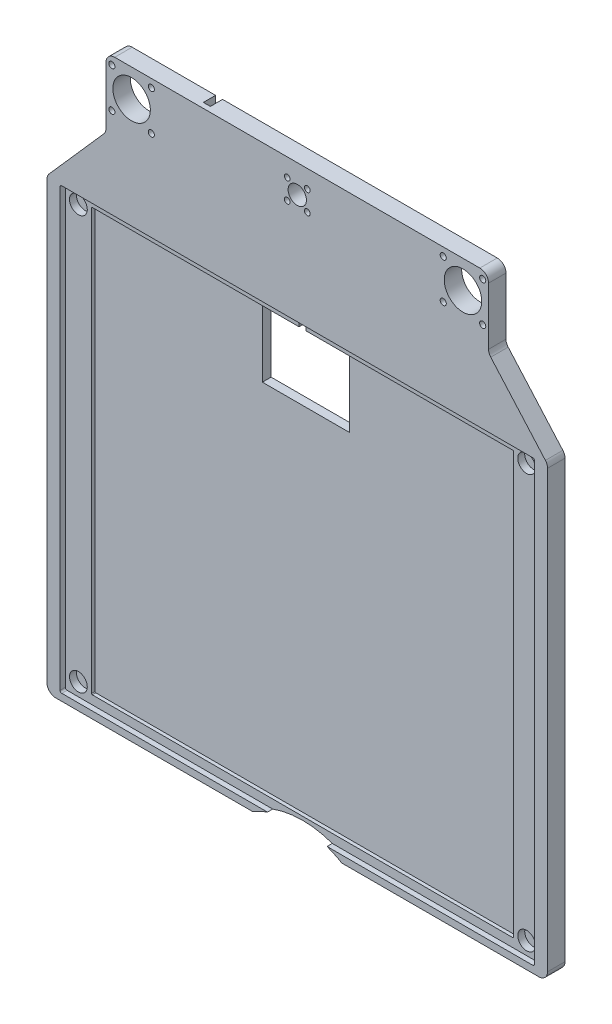
SolidWorks part; units mm, degrees
ref_plane "Alzado" through (0, 0, 0) normal (0, 0, 1) x (1, 0, 0)
ref_plane "Planta" through (0, 0, 0) normal (0, 1, 0) x (1, 0, 0)
ref_plane "Vista lateral" through (0, 0, 0) normal (1, 0, 0) x (0, 0, -1)
sketch "Model" plane through (0, 0, 0) normal (0, 0, 1) x (1, 0, 0)
  line L0 (-155.7898, 91.0382) -> (-155.7898, 58.2051)
  line L1 (-46.1298, -238.9618) -> (-46.1298, 159.2002) construction
  line L2 (-189.6298, 16.0382) -> (97.3702, 16.0382) construction
  line L3 (37.5552, 91.3532) -> (60.1852, 68.7232) construction
  line L4 (-129.8148, 91.3532) -> (-152.4448, 68.7232) construction
  line L5 (-141.1298, 80.0382) -> (48.8702, 80.0382) construction
  line L6 (-157.039, 54.8988) -> (64.7794, 54.8988) construction
  line L8 (63.5302, 58.2051) -> (63.5302, 91.0382)
  line L10 (96.121, 19.3445) -> (64.7794, 54.8988)
  line L14 (58.5302, 96.0382) -> (-150.7898, 96.0382)
  line L15 (-184.6298, -238.9618) -> (92.3702, -238.9618)
  line L16 (-189.6298, 16.0382) -> (-189.6298, -233.9618)
  line L17 (97.3702, 16.0382) -> (97.3702, -233.9618)
  line L91 (-188.3806, 19.3445) -> (-157.039, 54.8988)
  arc A0 (92.3702, -238.9618) -> (97.3702, -233.9618) centre (92.3702, -233.9618) ccw
  arc A1 (-189.6298, -233.9618) -> (-184.6298, -238.9618) centre (-184.6298, -233.9618) ccw
  arc A2 (-150.7898, 96.0382) -> (-155.7898, 91.0382) centre (-150.7898, 91.0382) ccw
  arc A3 (63.5302, 91.0382) -> (58.5302, 96.0382) centre (58.5302, 91.0382) ccw
  arc A4 (97.3702, 16.0382) -> (96.121, 19.3445) centre (92.3702, 16.0382) ccw
  arc A5 (-188.3806, 19.3445) -> (-189.6298, 16.0382) centre (-184.6298, 16.0382) ccw
  arc A6 (64.7794, 54.8988) -> (63.5302, 58.2051) centre (68.5302, 58.2051) cw
  arc A7 (-157.039, 54.8988) -> (-155.7898, 58.2051) centre (-160.7898, 58.2051) ccw
  circle A8 centre (48.8702, 80.0382) radius 10.75
  circle A9 centre (37.5552, 68.7232) radius 1.75
  circle A10 centre (60.1852, 68.7232) radius 1.75
  circle A11 centre (60.1852, 91.3532) radius 1.75
  circle A12 centre (37.5552, 91.3532) radius 1.75
  circle A13 centre (-129.8148, 91.3532) radius 1.75
  circle A14 centre (-152.4448, 91.3532) radius 1.75
  circle A15 centre (-152.4448, 68.7232) radius 1.75
  circle A16 centre (-129.8148, 68.7232) radius 1.75
  circle A17 centre (-141.1298, 80.0382) radius 10.75
  circle A18 centre (-46.1298, 80.0382) radius 5.25
  circle A19 centre (-51.8798, 85.7882) radius 1.65
  circle A20 centre (-40.3798, 85.7882) radius 1.65
  circle A21 centre (-40.3798, 74.2882) radius 1.65
  circle A22 centre (-51.8798, 74.2882) radius 1.65
  dimension "D1" = 5
  dimension "D2" = 5
  dimension "D3" = 5
  dimension "D13" = 5
  dimension "D14" = 5
  dimension "D15" = 5
  dimension "D18" = 5
  dimension "D19" = 5
  dimension "D20" = 21.5
  dimension "D8" = 3.5
  dimension "D5" = 10.5
  dimension "D7" = 3.3
  dimension "D4" = 287
  dimension "D16" = 48.603
  dimension "D6" = 95
  dimension "D12" = 5.75
  dimension "D22" = 5.75
  dimension "D23" = 11.315
  dimension "D24" = 11.315
  dimension "D25" = 16
  dimension "D26" = 335
  dimension "D27" = 109.66
  dimension "D28" = 109.66
  dimension "D29" = 255
  dimension "D17" = 48.603
  dimension "D9" = 2
  dimension "D21" = 2
  dimension "D10" = 2
  dimension "D11" = 2
extrude "Saliente-Extruir1" add sketch "Model" along normal blind 10
sketch "Croquis1" plane through (0, 0, 10) normal (0, 0, 1) x (1, 0, 0)
  line L0 (-46.1298, -238.9618) -> (-46.1298, 96.0382) construction
  line L1 (-184.6298, -238.9618) -> (92.3702, -238.9618) construction
  line L2 (58.5302, 96.0382) -> (-150.7898, 96.0382) construction
  line L3 (-189.6298, -108.9618) -> (97.3702, -108.9618) construction
  line L4 (-189.6298, 16.0382) -> (-189.6298, -233.9618) construction
  line L5 (97.3702, -233.9618) -> (97.3702, 16.0382) construction
  line L6 (-167.1298, -229.4618) -> (-167.1298, 11.5382)
  line L7 (-166.6298, -229.9618) -> (74.3702, -229.9618)
  line L8 (-166.6298, 12.0382) -> (74.3702, 12.0382)
  line L9 (74.8702, -229.4618) -> (74.8702, 11.5382)
  line L10 (-167.1298, -229.9618) -> (74.8702, 12.0382) construction
  line L11 (-167.1298, 12.0382) -> (74.8702, -229.9618) construction
  arc A0 (74.8702, 11.5382) -> (74.3702, 12.0382) centre (74.3702, 11.5382) ccw
  arc A1 (-166.6298, 12.0382) -> (-167.1298, 11.5382) centre (-166.6298, 11.5382) ccw
  arc A2 (74.8702, -229.4618) -> (74.3702, -229.9618) centre (74.3702, -229.4618) cw
  arc A3 (-167.1298, -229.4618) -> (-166.6298, -229.9618) centre (-166.6298, -229.4618) ccw
  point P13 (-46.1298, -108.9618)
  dimension "D3" = 0.5
  dimension "D4" = 0.5
  dimension "D5" = 0.5
  dimension "D1" = 242
  dimension "D2" = 242
extrude "Cortar-Extruir1" cut sketch "Croquis1" against normal blind 5
sketch "Croquis2" plane through (0, 0, 10) normal (0, 0, 1) x (1, 0, 0)
  line L0 (-46.1298, 96.0382) -> (-46.1298, -238.9618) construction
  line L1 (58.5302, 96.0382) -> (-150.7898, 96.0382) construction
  line L2 (-184.6298, -238.9618) -> (92.3702, -238.9618) construction
  line L3 (-189.6298, -108.9618) -> (97.3702, -108.9618) construction
  line L4 (-189.6298, 16.0382) -> (-189.6298, -233.9618) construction
  line L5 (97.3702, -233.9618) -> (97.3702, 16.0382) construction
  line L6 (-182.1298, -233.9618) -> (-182.1298, 16.0382)
  line L7 (-181.1298, -234.9618) -> (88.8702, -234.9618)
  line L8 (-181.1298, 17.0382) -> (88.8702, 17.0382)
  line L9 (89.8702, -233.9618) -> (89.8702, 16.0382)
  line L10 (-182.1298, -234.9618) -> (89.8702, 17.0382) construction
  line L11 (-182.1298, 17.0382) -> (89.8702, -234.9618) construction
  arc A0 (-182.1298, -233.9618) -> (-181.1298, -234.9618) centre (-181.1298, -233.9618) ccw
  arc A1 (88.8702, -234.9618) -> (89.8702, -233.9618) centre (88.8702, -233.9618) ccw
  arc A2 (89.8702, 16.0382) -> (88.8702, 17.0382) centre (88.8702, 16.0382) ccw
  arc A3 (-181.1298, 17.0382) -> (-182.1298, 16.0382) centre (-181.1298, 16.0382) ccw
  point P13 (-46.1298, -108.9618)
  dimension "D3" = 1
  dimension "D1" = 252
  dimension "D2" = 272
extrude "Cortar-Extruir2" cut sketch "Croquis2" against normal blind 3
sketch "Croquis3" plane through (0, 0, 7) normal (0, 0, 1) x (1, 0, 0)
  line L0 (-167.1298, -229.4618) -> (-167.1298, 11.5382) construction
  line L1 (-182.1298, 16.0382) -> (-182.1298, -233.9618) construction
  line L2 (-181.1298, -234.9618) -> (88.8702, -234.9618) construction
  line L3 (-167.1298, -229.4618) -> (-167.1298, 11.5382) construction
  line L4 (-182.1298, 16.0382) -> (-182.1298, -233.9618) construction
  line L5 (-181.1298, -234.9618) -> (88.8702, -234.9618) construction
  line L6 (-46.1298, -238.9618) -> (-46.1298, 96.0382) construction
  line L7 (-184.6298, -238.9618) -> (92.3702, -238.9618) construction
  line L8 (58.5302, 96.0382) -> (-150.7898, 96.0382) construction
  line L9 (-189.6298, -108.9618) -> (97.3702, -108.9618) construction
  line L10 (-189.6298, 16.0382) -> (-189.6298, -233.9618) construction
  line L11 (97.3702, -233.9618) -> (97.3702, 16.0382) construction
  circle A0 centre (-174.6298, -227.4618) radius 5.1
  circle A1 centre (82.3702, -227.4618) radius 5.1
  circle A2 centre (-174.6298, 9.5382) radius 5.1
  circle A3 centre (82.3702, 9.5382) radius 5.1
  dimension "D2" = 10.2
  dimension "D1" = 15
  dimension "D3" = 7.5
  dimension "D4" = 7.5
extrude "Cortar-Extruir3" cut sketch "Croquis3" against normal blind 4 contours A0
sketch "Croquis4" plane through (0, 0, 0) normal (0, 0, -1) x (-1, 0, 0)
  line L0 (46.1298, 166.123) -> (46.1298, -168.877) construction
  line L3 (184.6298, -238.9618) -> (-92.3702, -238.9618) construction
  circle A0 centre (46.1298, -281.9618) radius 50
  dimension "D1" = 100
  dimension "D2" = 43
extrude "Cortar-Extruir4" cut sketch "Croquis4" against normal up to next
sketch "Croquis5" plane through (0, 0, 7) normal (0, 0, 1) x (1, 0, 0)
  line L0 (-166.6298, 12.0382) -> (74.3702, 12.0382) construction
  line L1 (-166.6298, 12.0382) -> (74.3702, 12.0382) construction
  line L2 (-46.1298, 96.0382) -> (-46.1298, -229.9618) construction
  line L3 (58.5302, 96.0382) -> (-150.7898, 96.0382) construction
  line L4 (-166.6298, -229.9618) -> (74.3702, -229.9618) construction
  line L5 (-71.1298, -27.9618) -> (-71.1298, 12.0382)
  line L6 (-71.1298, -27.9618) -> (-21.1298, -27.9618)
  line L7 (-71.1298, 12.0382) -> (-21.1298, 12.0382) construction
  line L8 (-21.1298, -27.9618) -> (-21.1298, 12.0382)
  line L9 (-71.1298, -27.9618) -> (-21.1298, 12.0382) construction
  line L10 (-71.1298, 12.0382) -> (-21.1298, -27.9618) construction
  line L11 (-46.1298, 96.0382) -> (-155.7898, 96.0382) construction
  line L12 (-155.7898, 91.0382) -> (-155.7898, 58.2051) construction
  line L13 (-155.7898, 96.0382) -> (-155.7898, 12.0382) construction
  line L14 (-155.7898, 58.2051) -> (-46.1298, 58.2051) construction
  line L15 (-100.9598, 96.0382) -> (-100.9598, 83.2051) construction
  line L16 (-75.9598, 58.2051) -> (-71.1298, 58.2051) construction
  line L17 (-46.1298, 33.2051) -> (-46.1298, 12.0382) construction
  line L18 (-102.9598, 96.0382) -> (-102.9598, 83.2051)
  line L19 (-75.9598, 56.2051) -> (-71.1298, 56.2051)
  line L20 (-48.1298, 33.2051) -> (-48.1298, 12.0382)
  line L21 (-98.9598, 96.0382) -> (-98.9598, 83.2051)
  line L22 (-75.9598, 60.2051) -> (-71.1298, 60.2051)
  line L23 (-44.1298, 33.2051) -> (-44.1298, 12.0382)
  line L24 (-102.9598, 96.0382) -> (-98.9598, 96.0382)
  line L25 (-71.1298, 12.0382) -> (-48.1298, 12.0382)
  line L26 (-44.1298, 12.0382) -> (-21.1298, 12.0382)
  arc A0 (-46.1298, 33.2051) -> (-71.1298, 58.2051) centre (-71.1298, 33.2051) ccw construction
  arc A1 (-75.9598, 58.2051) -> (-100.9598, 83.2051) centre (-75.9598, 83.2051) cw construction
  arc A2 (-75.9598, 56.2051) -> (-102.9598, 83.2051) centre (-75.9598, 83.2051) cw
  arc A3 (-48.1298, 33.2051) -> (-71.1298, 56.2051) centre (-71.1298, 33.2051) ccw
  arc A4 (-75.9598, 60.2051) -> (-98.9598, 83.2051) centre (-75.9598, 83.2051) cw
  arc A5 (-44.1298, 33.2051) -> (-71.1298, 60.2051) centre (-71.1298, 33.2051) ccw
  point P9 (-46.1298, -7.9618)
  point P28 (-100.9598, 58.2051)
  dimension "D3" = 25
  dimension "D1" = 40
  dimension "D2" = 50
  dimension "D4" = 2
  dimension "D5" = 2
extrude "Cortar-Extruir5" cut sketch "Croquis5" against normal up to next
equation "\"D12@Model\"=11.5/2"
equation "\"D22@Model\"=11.5/2"
equation "\"D28@Model\"=\"D27@Model\""
equation "\"D17@Model\"=\"D16@Model\""
